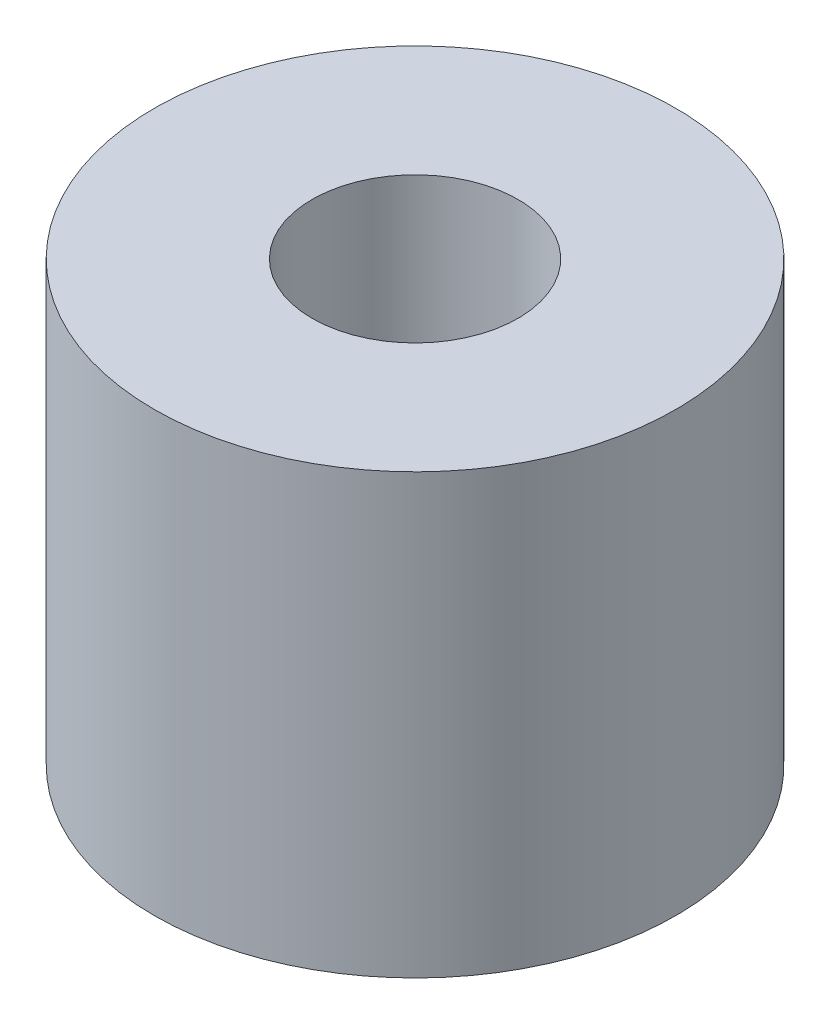
SolidWorks part; units mm, degrees
material "ABS"
ref_plane "Front Plane" through (0, 0, 0) normal (0, 0, 1) x (1, 0, 0)
ref_plane "Top Plane" through (0, 0, 0) normal (0, 1, 0) x (1, 0, 0)
ref_plane "Right Plane" through (0, 0, 0) normal (1, 0, 0) x (0, 0, -1)
sketch "Sketch1" plane through (0, 0, 0) normal (0, 1, 0) x (1, 0, 0)
  circle A0 centre (0, 0) radius 1.175
  circle A1 centre (0, 0) radius 2.975
  dimension "D1" = 2.35
  dimension "D2" = 1.8
extrude "Boss-Extrude1" add sketch "Sketch1" along normal blind 5
